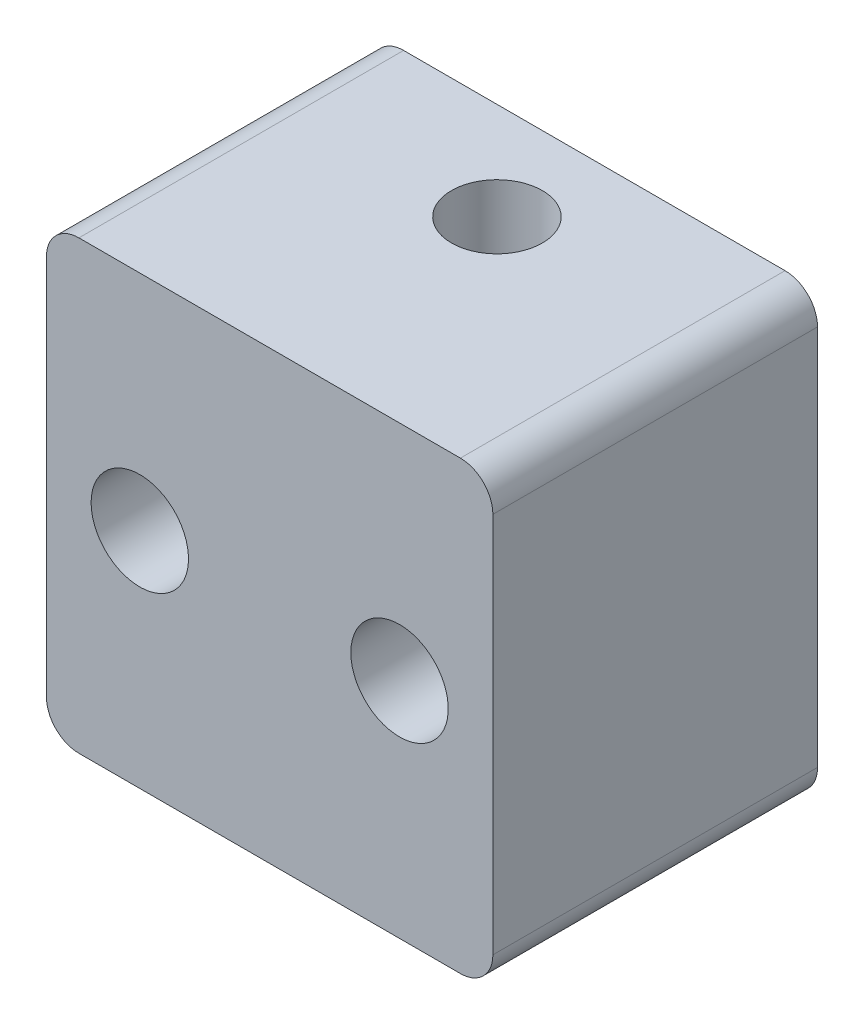
SolidWorks part; units mm, degrees
ref_plane "Front Plane" through (0, 0, 0) normal (0, 0, 1) x (1, 0, 0)
ref_plane "Top Plane" through (0, 0, 0) normal (0, 1, 0) x (1, 0, 0)
ref_plane "Right Plane" through (0, 0, 0) normal (1, 0, 0) x (0, 0, -1)
sketch "Sketch1" plane through (0, 0, 0) normal (0, 0, 1) x (1, 0, 0)
  line L1 (-6.875, -6.875) -> (6.875, -6.875)
  line L2 (-6.875, -6.875) -> (-6.875, 6.875)
  line L3 (-6.875, 6.875) -> (6.875, 6.875)
  line L4 (6.875, -6.875) -> (6.875, 6.875)
  line L5 (-6.875, -6.875) -> (6.875, 6.875) construction
  line L6 (-6.875, 6.875) -> (6.875, -6.875) construction
  point P0 (0, 0)
  dimension "D1" = 13.75
extrude "Boss-Extrude1" add sketch "Sketch1" along normal up to surface (10 mm away)
sketch "Sketch2" plane through (0, 0, 0) normal (0, 0, -1) x (-1, 0, 0)
  circle A0 centre (4, 0) radius 1.5 construction
  circle A1 centre (-4, 0) radius 1.5 construction
  circle A2 centre (4, 0) radius 1.5
  circle A3 centre (-4, 0) radius 1.5
sketch "Sketch3" plane through (0, 6.875, 0) normal (0, 1, 0) x (1, 0, 0)
  line L0 (0, -3) -> (0, 0) construction
  circle A0 centre (0, -3) radius 1.4
  dimension "D1" = 2.8
  dimension "D2" = 3
extrude "Cut-Extrude1" cut sketch "Sketch3" against normal through all
extrude "Cut-Extrude2" cut sketch "Sketch2" against normal through all
fillet "Fillet1" radius 1 4 edges at (-6.875, -6.875, 5) (6.875, -6.875, 5) (6.875, 6.875, 5) (-6.875, 6.875, 5)
